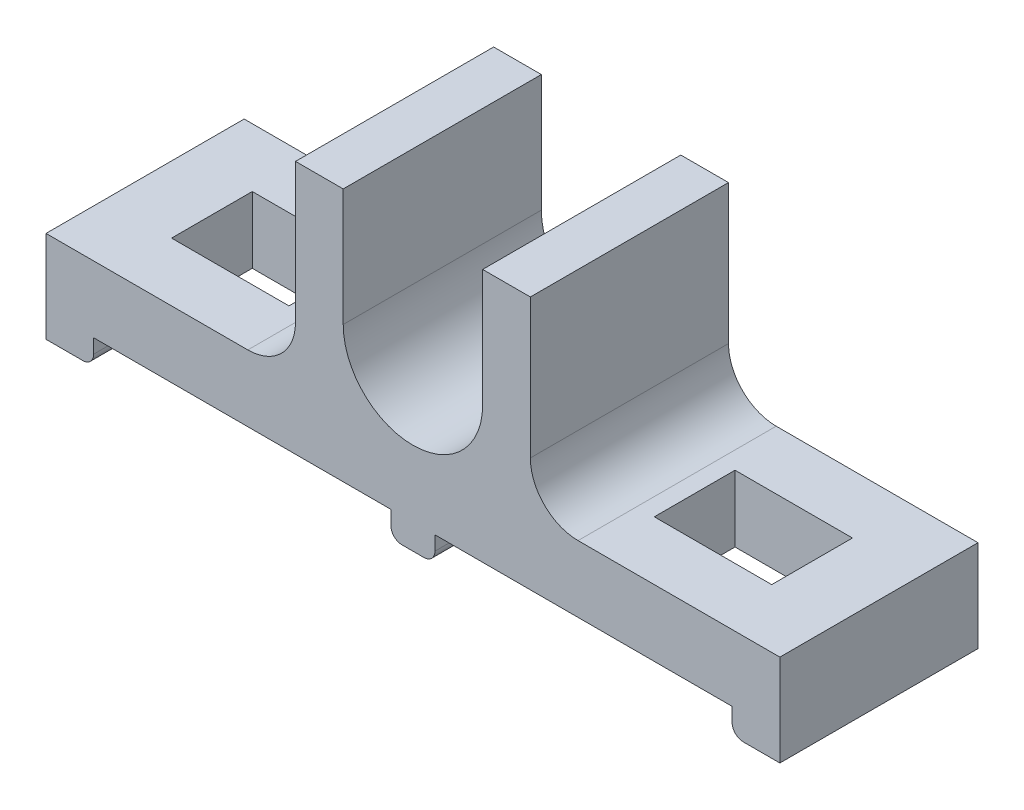
SolidWorks part; units mm, degrees
ref_plane "Front Plane" through (0, 0, 0) normal (0, 0, 1) x (1, 0, 0)
ref_plane "Top Plane" through (0, 0, 0) normal (0, 1, 0) x (1, 0, 0)
ref_plane "Right Plane" through (0, 0, 0) normal (1, 0, 0) x (0, 0, -1)
sketch "Sketch1" plane through (0, 0, 0) normal (0, 0, 1) x (1, 0, 0)
  line L0 (100, 25) -> (100, -64.7443) construction
  line L1 (0, 0) -> (10, 0)
  line L2 (0, 0) -> (0, 25)
  line L3 (0, 25) -> (55, 25)
  line L4 (200, 0) -> (200, 25)
  line L5 (97, 0) -> (103, 0)
  line L7 (13, 3) -> (13, 6.8676)
  line L8 (13, 6.8676) -> (94, 6.8676)
  line L9 (94, 3) -> (94, 6.8676)
  line L10 (145, 25) -> (200, 25)
  line L12 (81, 44) -> (81, 76)
  line L13 (81, 76) -> (68, 76)
  line L14 (68, 38) -> (68, 76)
  line L15 (119, 76) -> (132, 76)
  line L16 (119, 44) -> (119, 76)
  line L17 (132, 38) -> (132, 76)
  line L18 (187, 3) -> (187, 6.8676)
  line L19 (106, 3) -> (106, 6.8676)
  line L20 (187, 6.8676) -> (106, 6.8676)
  line L21 (190, 0) -> (200, 0)
  arc A0 (13, 3) -> (10, 0) centre (10, 3) cw
  arc A1 (94, 3) -> (97, 0) centre (97, 3) ccw
  arc A2 (68, 38) -> (55, 25) centre (55, 38) cw
  arc A3 (81, 44) -> (119, 44) centre (100, 44) ccw
  arc A4 (132, 38) -> (145, 25) centre (145, 38) ccw
  arc A5 (106, 3) -> (103, 0) centre (103, 3) cw
  arc A6 (187, 3) -> (190, 0) centre (190, 3) ccw
  point P23 (81, 25)
  dimension "D3" = 3
  dimension "D4" = 3
  dimension "D2" = 13
  dimension "D5" = 19
  dimension "D1" = 25
  dimension "D6" = 13
  dimension "D7" = 10
  dimension "D8" = 6
  dimension "D9" = 32
extrude "Boss-Extrude1" add sketch "Sketch1" along normal mid plane 54
ref_plane "Plane1" through (100, 0, 0) normal (1, 0, 0) x (0, 0, -1)
sketch "Sketch2" plane through (0, 25, 0) normal (0, 1, 0) x (1, 0, 0)
  line L0 (55, -27) -> (0, -27) construction
  line L1 (18.218, 11) -> (50.218, 11)
  line L2 (18.218, 11) -> (18.218, -11)
  line L3 (18.218, -11) -> (50.218, -11)
  line L4 (50.218, 11) -> (50.218, -11)
  dimension "D1" = 32
  dimension "D2" = 43.782
  dimension "D3" = 16
  dimension "D4" = 22
extrude "Cut-Extrude1" cut sketch "Sketch2" against normal through all
mirror "Mirror1" about plane through (100, 0, 0) normal (1, 0, 0) of "Cut-Extrude1"
